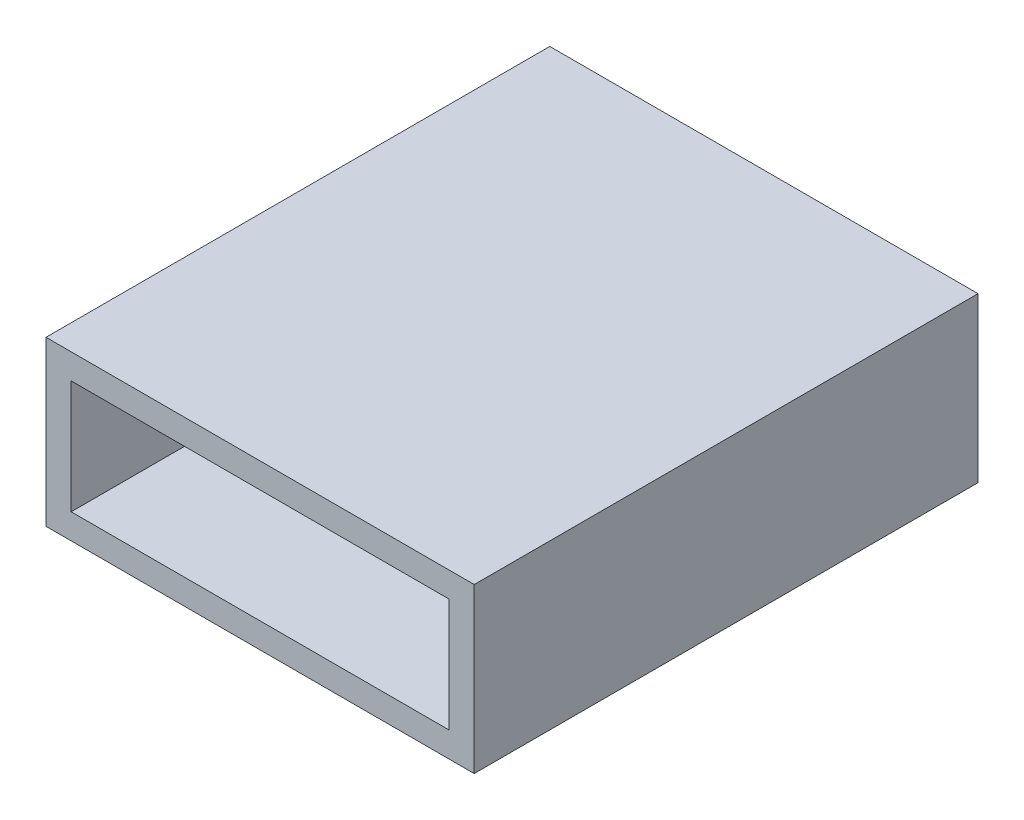
SolidWorks part; units mm, degrees
ref_plane "Top Plane" through (0, 0, 0) normal (0, 0, 1) x (1, 0, 0)
ref_plane "Right Plane" through (0, 0, 0) normal (0, 1, 0) x (1, 0, 0)
ref_plane "Front Plane" through (0, 0, 0) normal (1, 0, 0) x (0, 0, -1)
sketch "Sketch1" plane through (0, 0, 0) normal (0, 0, 1) x (1, 0, 0)
  line L0 (-17, 6.5) -> (-17, -6.5)
  line L1 (-15, 4.5) -> (15, 4.5)
  line L2 (-15, 4.5) -> (-15, -4.5)
  line L3 (-15, -4.5) -> (15, -4.5)
  line L4 (15, 4.5) -> (15, -4.5)
  line L5 (-15, 4.5) -> (15, -4.5) construction
  line L6 (-15, -4.5) -> (15, 4.5) construction
  line L7 (-17, -6.5) -> (-5.5, -6.5)
  line L8 (17, 6.5) -> (17, -6.5)
  line L9 (-17, 6.5) -> (17, 6.5)
  line L10 (0, -5.5) -> (0, -4.5) construction
  line L11 (-5.5, -5.5) -> (5.5, -5.5)
  line L12 (-5.5, -5.5) -> (-5.5, -6.5)
  line L14 (5.5, -5.5) -> (5.5, -6.5)
  line L15 (5.5, -6.5) -> (17, -6.5)
  line L17 (-17, -6.5) -> (17, -6.5) construction
  point P4 (0, 0)
  dimension "D1" = 9
  dimension "D2" = 30
  dimension "D4" = 1
  dimension "D5" = 11
  dimension "D3" = 2
extrude "Boss-Extrude1" add sketch "Sketch1" along normal blind 4
sketch "Sketch2" plane through (0, 0, 4) normal (0, 0, 1) x (1, 0, 0)
  line L1 (-17, 6.5) -> (17, 6.5)
  line L2 (-17, 6.5) -> (-17, -6.5)
  line L3 (-17, -6.5) -> (17, -6.5)
  line L4 (17, 6.5) -> (17, -6.5)
  line L5 (-15, 4.5) -> (15, 4.5)
  line L6 (-15, 4.5) -> (-15, -4.5)
  line L7 (-15, -4.5) -> (15, -4.5)
  line L8 (15, 4.5) -> (15, -4.5)
extrude "Boss-Extrude2" add sketch "Sketch2" along normal blind 36
